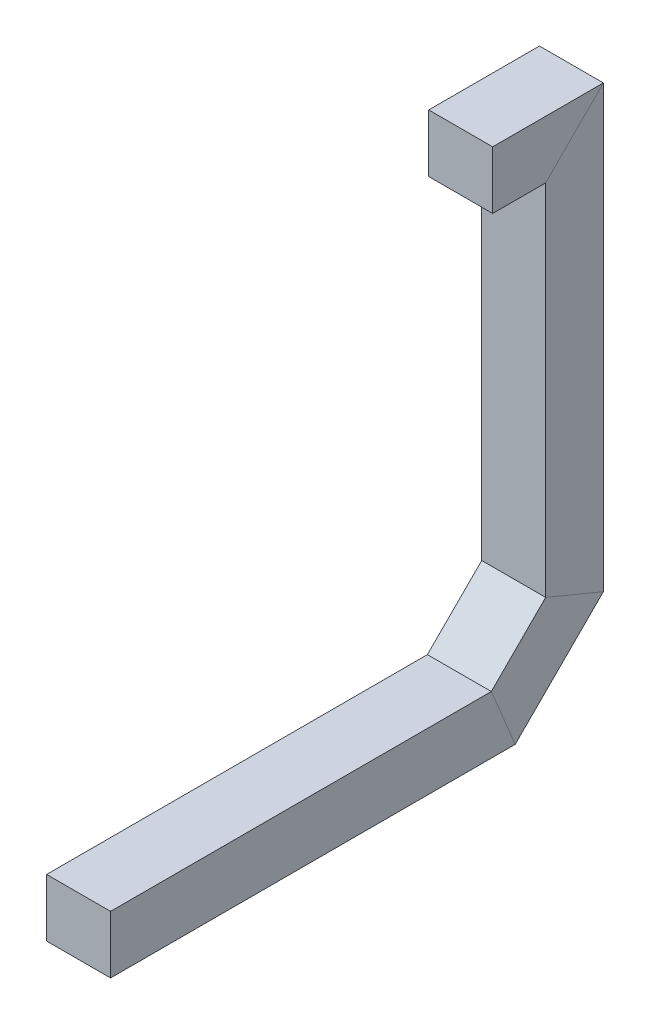
SolidWorks part; units mm, degrees
ref_plane "Front Plane" through (0, 0, 0) normal (0, 0, 1) x (1, 0, 0)
ref_plane "Top Plane" through (0, 0, 0) normal (0, 1, 0) x (1, 0, 0)
ref_plane "Right Plane" through (0, 0, 0) normal (1, 0, 0) x (0, 0, -1)
sketch "Sketch1" plane through (0, 0, 0) normal (1, 0, 0) x (0, 0, -1)
  line L0 (0, 0) -> (-2387.6, 0)
  line L3 (0, 0) -> (431.8, 431.8)
  line L4 (431.8, 431.8) -> (431.8, 2860.04)
  line L5 (431.8, 2860.04) -> (-63.5, 2860.04)
  line L6 (1.0521, -2.54) -> (-2387.6, -2.54)
  line L7 (1.0521, -2.54) -> (434.34, 430.7479)
  line L8 (434.34, 430.7479) -> (434.34, 2862.58)
  line L9 (434.34, 2862.58) -> (-63.5, 2862.58)
  point P11 (0, 0)
  dimension "D1" = 2387.6
  dimension "D2" = 431.8
  dimension "D3" = 2428.24
  dimension "D4" = 495.3
  dimension "D5" = 2.54
sketch "Sketch2" plane through (0, 0, 0) normal (0, 0, 1) x (1, 0, 0)
  line L0 (0, 430.7479) -> (0, 2862.58) construction
  line L1 (-194.4067, 3038.1209) -> (194.4067, 3038.1209)
  line L2 (-194.4067, 3038.1209) -> (-194.4067, 2687.0391)
  line L3 (-194.4067, 2687.0391) -> (194.4067, 2687.0391)
  line L4 (194.4067, 3038.1209) -> (194.4067, 2687.0391)
  line L5 (-194.4067, 3038.1209) -> (194.4067, 2687.0391) construction
  line L6 (-194.4067, 2687.0391) -> (194.4067, 3038.1209) construction
  point P0 (0, 2862.58)
  point P7 (0, 0)
sweep "Sweep1" add profiles "Sketch2" path "Sketch1"
